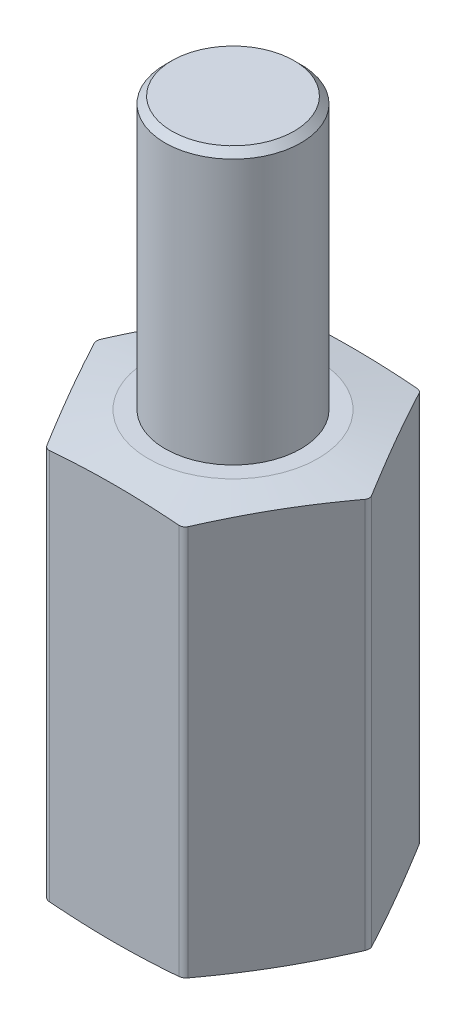
SolidWorks part; units mm, degrees
material "黄铜"
ref_plane "前视基准面" through (0, 0, 0) normal (0, 0, 1) x (1, 0, 0)
ref_plane "上视基准面" through (0, 0, 0) normal (0, 1, 0) x (1, 0, 0)
ref_plane "右视基准面" through (0, 0, 0) normal (1, 0, 0) x (0, 0, -1)
sketch "草图1" plane through (0, 0, 0) normal (0, 1, 0) x (1, 0, 0)
  line L1 (4.0415, 0) -> (2.0207, 3.5)
  line L2 (2.0207, 3.5) -> (-2.0207, 3.5)
  line L3 (-2.0207, 3.5) -> (-4.0415, 0)
  line L4 (-4.0415, 0) -> (-2.0207, -3.5)
  line L5 (-2.0207, -3.5) -> (2.0207, -3.5)
  line L6 (2.0207, -3.5) -> (4.0415, 0)
  circle A0 centre (0, 0) radius 3.5 construction
  dimension "六角对边距离" = 7
extrude "凸台-拉伸1" add sketch "草图1" along normal mid plane 12
fillet "圆角1" radius 0.2 6 edges at (2.0207, 0, -3.5) (-4.0415, 0, 0) (-2.0207, 0, -3.5) (-2.0207, 0, 3.5) (4.0415, 0, 0) (2.0207, 0, 3.5)
sketch "草图3" plane through (0, -6, 0) normal (0, 1, 0) x (1, 0, 0)
  circle A0 centre (0, 0) radius 2
  dimension "螺纹公称尺寸" = 4
extrude "切除-拉伸1" cut sketch "草图3" along normal blind 8
sketch "草图4" plane through (0, 0, 0) normal (0, 0, 1) x (1, 0, 0)
  line L0 (-2, 6) -> (-4.0105, 6) construction
  line L1 (-1.9053, 6) -> (1.9053, 6) construction
  line L2 (-4.0105, 6) -> (-4.0105, 5.75)
  line L4 (-4.0105, 6) -> (-4.0105, -6) construction
  line L5 (-2, 0.161) -> (-2, 8.9742) construction
  line L9 (-4.0105, 5.75) -> (-2.5, 6)
  line L10 (-2.5, 6) -> (-4.0105, 6)
  line L11 (0, 0) -> (0, 6) construction
  dimension "D1" = 0.25
  dimension "D2" = 0.5
revolve "切除-旋转1" cut sketch "草图4" angle 360 about L11
mirror "镜向1" about plane through (0, 0, 0) normal (0, 1, 0) of "切除-旋转1"
sketch "草图5" plane through (0, 6, 0) normal (0, 1, 0) x (1, 0, 0)
  circle A0 centre (0, 0) radius 2
  circle A1 centre (0, 0) radius 2 construction
extrude "凸台-拉伸2" add sketch "草图5" along normal blind 8
chamfer "倒角1" distance 0.2 angle 45 1 edges at (0, 14, 2)
other "冻结***"
